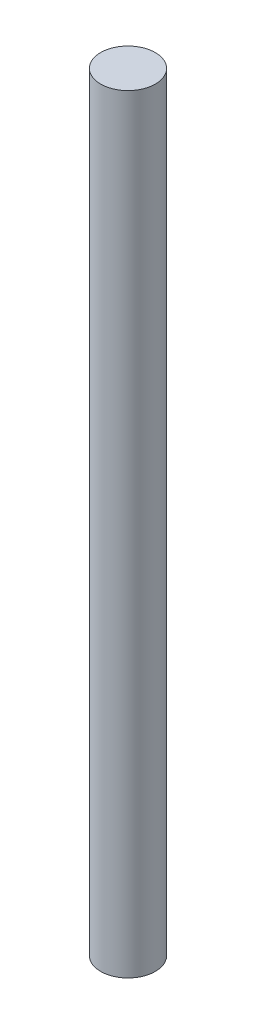
SolidWorks part; units mm, degrees
ref_plane "Front Plane" through (0, 0, 0) normal (0, 0, 1) x (1, 0, 0)
ref_plane "Top Plane" through (0, 0, 0) normal (0, 1, 0) x (1, 0, 0)
ref_plane "Right Plane" through (0, 0, 0) normal (1, 0, 0) x (0, 0, -1)
sketch "Sketch1" plane through (0, 0, 0) normal (0, 1, 0) x (1, 0, 0)
  circle A0 centre (0, 0) radius 4
  dimension "D1" = 8
extrude "Boss-Extrude1" add sketch "Sketch1" along normal blind 112.5
